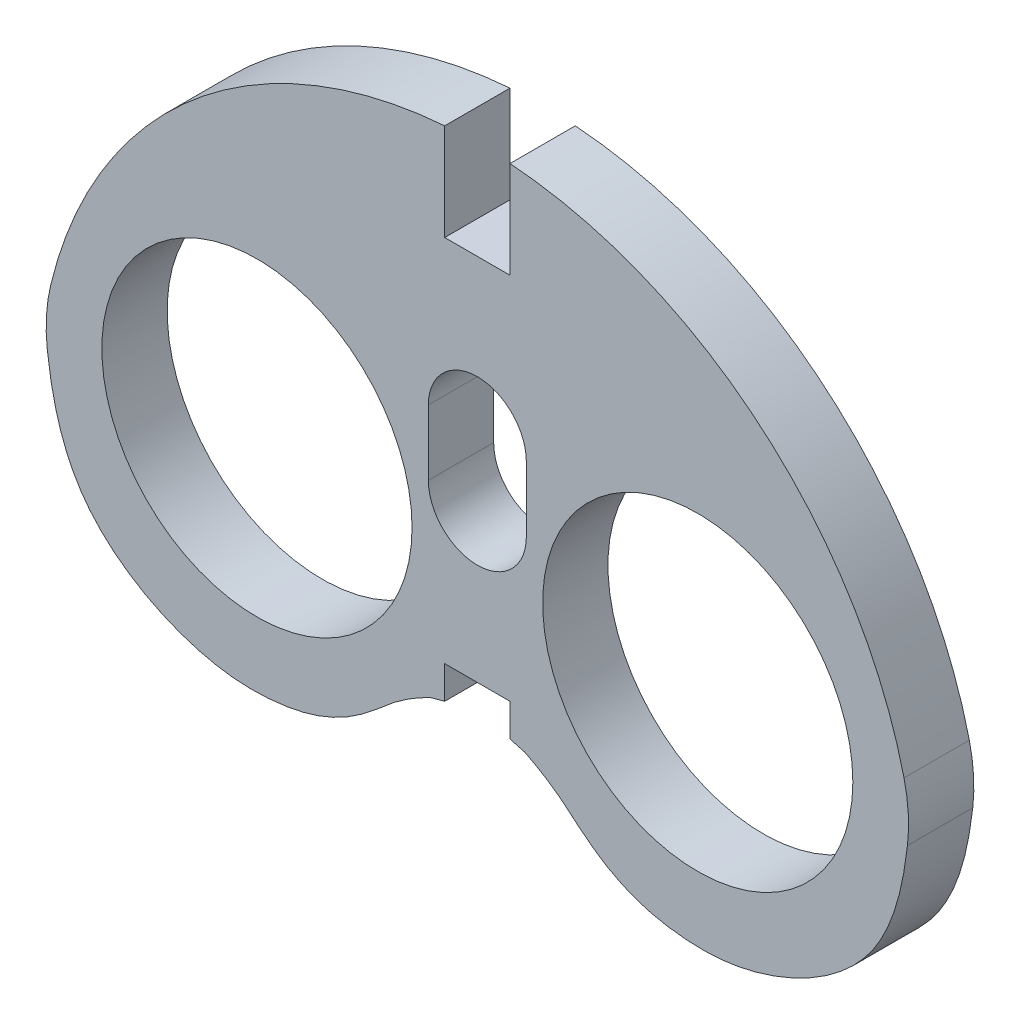
SolidWorks part; units mm, degrees
ref_plane "Piano frontale" through (0, 0, 0) normal (0, 0, 1) x (1, 0, 0)
ref_plane "Piano superiore" through (0, 0, 0) normal (0, 1, 0) x (1, 0, 0)
ref_plane "Piano destro" through (0, 0, 0) normal (1, 0, 0) x (0, 0, -1)
sketch "Schizzo1" plane through (0, 0, 0) normal (0, 0, 1) x (1, 0, 0)
  line L0 (-13.5, 0) -> (13.5, 0)
  line L1 (13.5, 0) -> (26.5, 0)
  line L2 (-13.5, 0) -> (-26.5, 0)
  line L3 (0, 3) -> (0, 7) construction
  line L4 (-3, 3) -> (-3, 7)
  line L5 (3, 3) -> (3, 7)
  line L6 (-2, 22.3794) -> (-2, 16.3794)
  line L7 (2, 22.3794) -> (-2, 22.3794)
  line L8 (-2, 16.3794) -> (2, 16.3794)
  line L9 (2, 16.3794) -> (2, 22.3794)
  line L10 (-2, -8.2222) -> (2, -8.2222)
  line L11 (-2, -8.2222) -> (-2, -6.2222)
  line L12 (-2, -6.2222) -> (2, -6.2222)
  line L13 (2, -6.2222) -> (2, -8.2222)
  circle A1 centre (-13.5, 0) radius 9.5
  circle A2 centre (13.5, 0) radius 9.5
  arc A3 (-26.5, 0) -> (26.5, 0) centre (0, -4.5) cw
  circle A4 centre (-13.5, 0) radius 12.5
  circle A5 centre (13.5, 0) radius 12.5
  arc A6 (-3, 3) -> (3, 3) centre (0, 3) ccw
  arc A7 (3, 7) -> (-3, 7) centre (0, 7) ccw
  spline S0 degree 2 poles (-6, -10) (0, -6) (6, -10) knots 0 0 0 1 1 1
  spline S1 degree 3 poles (-26.5, 0) (-26.2896, -2.9985) (-25.2189, -9.8819) (-17.2018, -13.6181) (-10.428, -13.4304) (-7.3468, -12.0113) (-4.7096, -9.3786) (-2.8915, -8.4645) knots 0 0 0 0 0.254741 0.563192 0.634676 0.898097 1 1 1 1
  spline S3 degree 3 poles (26.5, 0) (26.2896, -2.9985) (25.2188, -9.8819) (17.2019, -13.6181) (10.4278, -13.4304) (7.3501, -12.0118) (4.708, -9.3783) (2.8991, -8.4656) knots 0 0 0 0 0.254741 0.563192 0.634676 0.898097 1 1 1 1
  point P5 (0, 0)
  point P13 (0, 5)
  point P23 (0, 19.7172)
  point P26 (0, 0)
  point P29 (0, 0)
  dimension "D1" = 19
  dimension "D2" = 19
  dimension "D6" = 25
  dimension "D7" = 25
  dimension "D10" = 3
  dimension "D17" = 4.5
  dimension "D3" = 27
  dimension "D4" = 13
  dimension "D5" = 13
  dimension "D8" = 10
  dimension "D9" = 4
  dimension "D11" = 4
  dimension "D12" = 6
  dimension "D13" = 2
  dimension "D14" = 8
  dimension "D15" = 2
  dimension "D16" = 13.5
extrude "Estrusione-Estrusione1" add sketch "Schizzo1" along normal blind 4
fillet "Raccordo1" radius 10 3 edges at (-26.5, 0, 2)
fillet "Raccordo2" radius 10 3 edges at (26.5, 0, 2)
